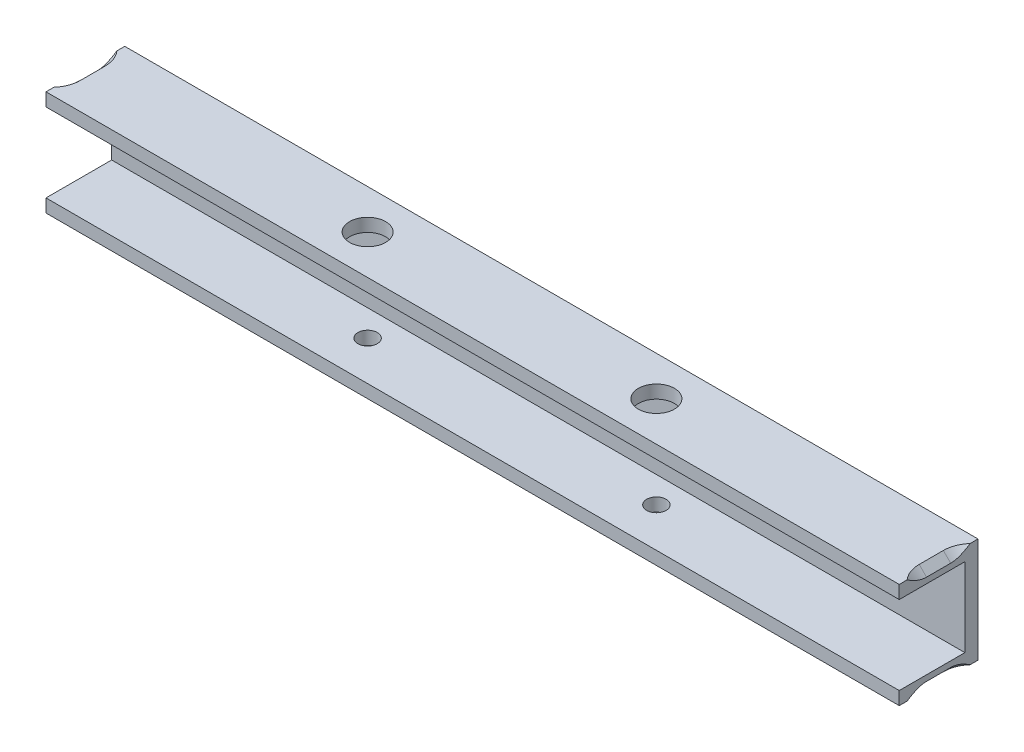
SolidWorks part; units mm, degrees
material "ASTM A36 Steel"
ref_plane "Front Plane" through (0, 0, 0) normal (0, 0, 1) x (1, 0, 0)
ref_plane "Top Plane" through (0, 0, 0) normal (0, 1, 0) x (1, 0, 0)
ref_plane "Right Plane" through (0, 0, 0) normal (1, 0, 0) x (0, 0, -1)
sketch "Sketch1" plane through (0, 0, 0) normal (1, 0, 0) x (0, 0, -1)
  line L0 (0, 25.4) -> (-19.05, 25.4)
  line L1 (-19.05, 25.4) -> (-19.05, 22.225)
  line L2 (-19.05, 22.225) -> (-3.175, 22.225)
  line L3 (-3.175, 22.225) -> (-3.175, 3.175)
  line L4 (-3.175, 3.175) -> (-19.05, 3.175)
  line L5 (-19.05, 3.175) -> (-19.05, 0)
  line L6 (-19.05, 0) -> (0, 0)
  line L7 (0, 0) -> (0, 25.4)
  dimension "D1" = 3.175
  dimension "D2" = 3.175
  dimension "D3" = 25.4
  dimension "D4" = 19.05
extrude "Boss-Extrude1" add sketch "Sketch1" along normal mid plane 206.375
sketch "Sketch2" plane through (0, 0, 0) normal (0, 0, 1) x (1, 0, 0)
  line L0 (0, 32.1479) -> (0, 74.7653) construction
  line L1 (85.7123, 65.7648) -> (147.366, 65.7648)
  line L2 (85.7123, 65.7648) -> (85.7123, 23.8252)
  line L3 (85.7123, 23.8252) -> (147.366, 23.8252)
  line L4 (147.366, 65.7648) -> (147.366, 23.8252)
  line L5 (103.1875, 0) -> (103.1875, 25.4) construction
  line L6 (-147.366, 65.7648) -> (-147.366, 23.8252)
  line L7 (-85.7123, 23.8252) -> (-147.366, 23.8252)
  line L8 (-85.7123, 65.7648) -> (-85.7123, 23.8252)
  line L9 (-85.7123, 65.7648) -> (-147.366, 65.7648)
  dimension "D1" = 23.8252
  dimension "D2" = 17.4752
extrude "Cut-Extrude1" [suppressed] cut sketch "Sketch2" along normal through all
sketch "Sketch3" plane through (0, 0, 0) normal (0, -1, 0) x (1, 0, 0)
  circle A0 centre (34.925, 9.525) radius 2.3495
  circle A1 centre (-34.925, 9.525) radius 2.3495
  dimension "D1" = 4.699
  dimension "D2" = 9.525
  dimension "D3" = 34.925
  dimension "D4" = 34.925
extrude "Cut-Extrude2" cut sketch "Sketch3" against normal up to next
sketch "Sketch4" plane through (0, 25.4, 0) normal (0, 1, 0) x (1, 0, 0)
  circle A0 centre (-34.925, -9.525) radius 4.3663
  circle A1 centre (34.925, -9.525) radius 4.3663
  dimension "D1" = 8.7325
extrude "Cut-Extrude3" cut sketch "Sketch4" against normal up to next
sketch "Sketch5" plane through (0, 0, 0) normal (0, 0, -1) x (-1, 0, 0)
  circle A0 centre (-76.2, 15.875) radius 3.175
  circle A1 centre (76.2, 15.875) radius 3.175
  dimension "D3" = 15.875
  dimension "D4" = 6.35
  dimension "D1" = 76.2
  dimension "D2" = 76.2
extrude "Cut-Extrude4" cut sketch "Sketch5" against normal up to next
sketch "Sketch6" plane through (0, 25.4, 0) normal (0, 1, 0) x (1, 0, 0)
  line L0 (-111.0615, 0.508) -> (-108.5215, 0.508)
  line L1 (-101.4095, -6.604) -> (-101.4095, -12.446)
  line L2 (-108.5215, -19.558) -> (-111.0615, -19.558)
  line L3 (-103.1875, 0) -> (-103.1875, -19.05) construction
  arc A0 (-108.5215, 0.508) -> (-101.4095, -6.604) centre (-108.5215, -6.604) cw
  arc A1 (-101.4095, -12.446) -> (-108.5215, -19.558) centre (-108.5215, -12.446) cw
  point P8 (-101.4095, -9.525)
  dimension "D1" = 7.112
  dimension "D3" = 5.842
  dimension "D2" = 2.54
  dimension "D4" = 9.525
  dimension "D5" = 1.778
ref_plane "Plane1" through (-111.0615, 25.4, -0.508) normal (1, 0, 0) x (0, 0, -1)
sketch "Sketch7" plane through (-111.0615, 25.4, -0.508) normal (1, 0, 0) x (0, 0, -1)
  line L0 (-4.572, -4.572) -> (-4.572, 0.508)
  line L1 (-4.572, 0.508) -> (0.508, 0.508)
  line L2 (0.508, 0.508) -> (-4.572, -4.572)
  line L3 (-4.572, -20.828) -> (-4.572, -25.908)
  line L4 (-4.572, -25.908) -> (0.508, -25.908)
  line L5 (0.508, -25.908) -> (-4.572, -20.828)
  line L6 (-19.558, -25.4) -> (-0.508, -25.4) construction
  point P6 (0, -25.4)
  dimension "D1" = 0.508
  dimension "D2" = 5.08
sweep "Cut-Sweep1" cut profiles "Sketch7" path "Sketch6"
mirror "Mirror1" about plane through (0, 0, 0) normal (1, 0, 0) of "Cut-Sweep1"
sketch "Sketch8" plane through (0, 25.4, 0) normal (0, 1, 0) x (1, 0, 0)
  line L0 (-103.1875, 0) -> (-103.1875, -19.05)
sketch "Sketch9" plane through (0, 25.4, 0) normal (0, 1, 0) x (1, 0, 0)
  line L0 (103.1875, 0) -> (103.1875, -19.05)
  line L1 (103.1875, -17.1501) -> (103.1875, -19.05) construction
  line L2 (103.1875, -19.05) -> (-103.1875, -19.05) construction
